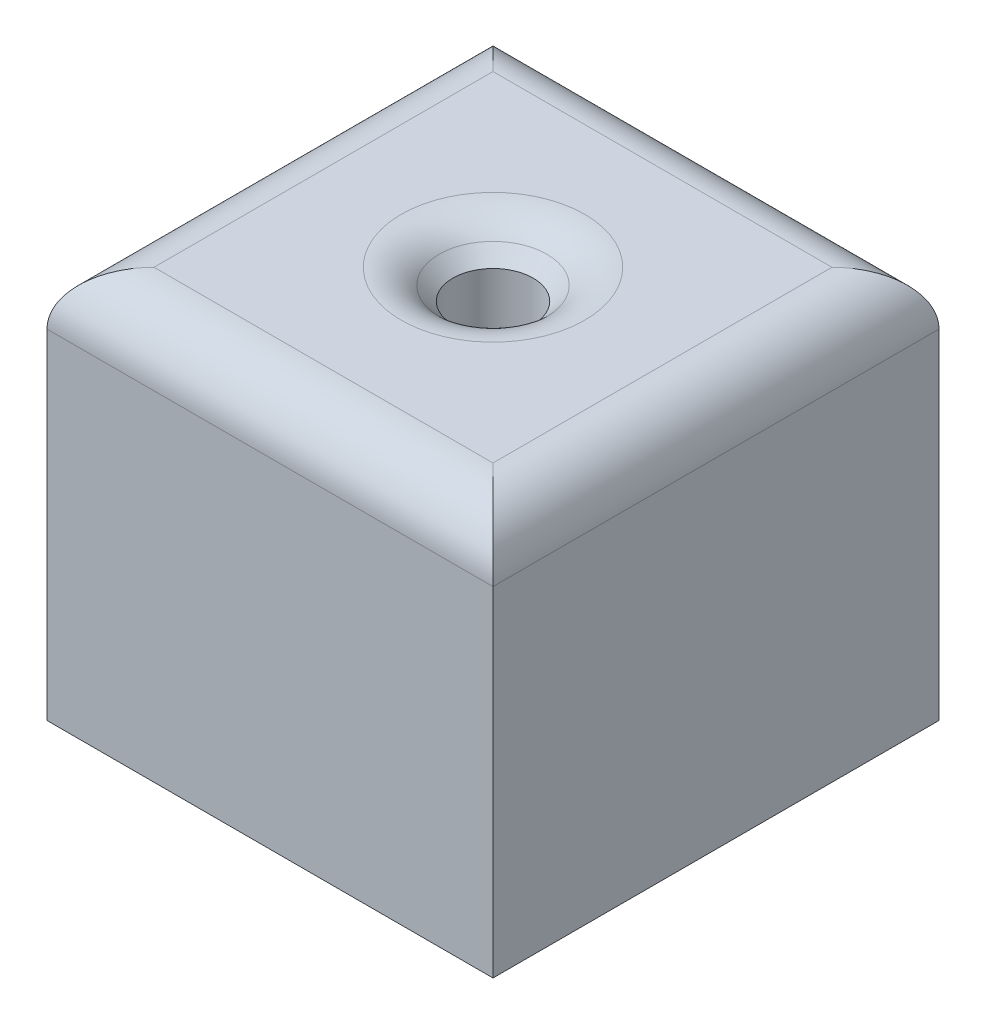
SolidWorks part; units mm, degrees
ref_plane "前视基准面" through (0, 0, 0) normal (0, 0, 1) x (1, 0, 0)
ref_plane "上视基准面" through (0, 0, 0) normal (0, 1, 0) x (1, 0, 0)
ref_plane "右视基准面" through (0, 0, 0) normal (1, 0, 0) x (0, 0, -1)
sketch "草图1" plane through (0, 0, 0) normal (0, 0, 1) x (1, 0, 0)
  line L1 (0, 0) -> (25, 0)
  line L2 (0, 0) -> (0, 25)
  line L3 (0, 25) -> (25, 25)
  line L4 (25, 0) -> (25, 25)
  dimension "D1" = 25
extrude "凸台-拉伸1" add sketch "草图1" along normal blind 25
ref_plane "基准面1" through (0, 0, 12.5) normal (0, 0, 1) x (1, 0, 0)
sketch "草图3" plane through (0, 0, 12.5) normal (0, 0, 1) x (1, 0, 0)
  line L0 (12.5, 25) -> (12.5, 0) construction
  line L3 (25, 25) -> (0, 25) construction
  line L4 (0, 0) -> (25, 0) construction
  line L5 (10.25, 23.35) -> (10.25, 0)
  line L6 (10.25, 23.35) -> (8.6, 25)
  line L7 (12.5, 0) -> (10.25, 0)
  line L8 (8.6, 25) -> (12.5, 25)
  line L9 (12.5, 25) -> (12.5, 0)
  dimension "D1" = 4.5
  dimension "D2" = 7.8
  dimension "D3" = 45
revolve "切除-旋转1" cut sketch "草图3" angle 360 about L9
ref_plane "基准面2" through (-8.3333, 8.3333, 8.3333) normal (0.5774, -0.5774, -0.5774) x (-0.8165, -0.4082, -0.4082)
ref_plane "基准面3" through (-12.5, 12.5, 0) normal (-0.7071, 0.7071, 0) x (0, 0, -1)
fillet "圆角1" radius 3 5 edges at (25, 25, 12.5) (12.5, 25, 25) (0, 25, 12.5) (12.5, 25, 0) (12.5, 25, 16.4)
chamfer "倒角1" distance 3 5 edges at (0, 0, 12.5) (12.5, 0, 25) (25, 0, 12.5) (12.5, 0, 0) (12.5, 0, 14.75)
